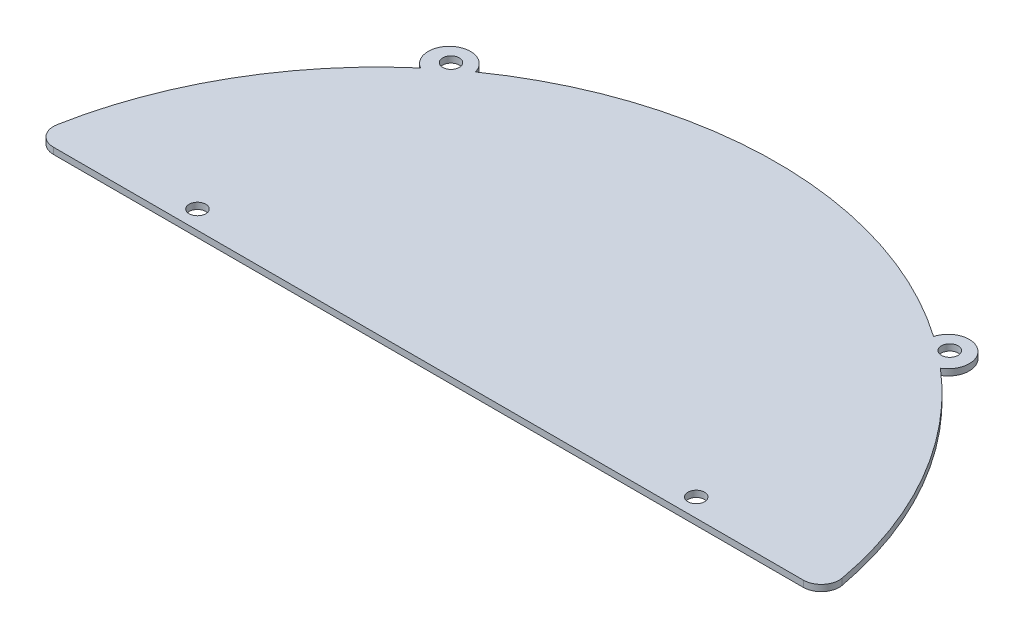
SolidWorks part; units mm, degrees
ref_plane "Plan de face" through (0, 0, 0) normal (0, 0, 1) x (1, 0, 0)
ref_plane "Plan de dessus" through (0, 0, 0) normal (0, 1, 0) x (1, 0, 0)
ref_plane "Plan de droite" through (0, 0, 0) normal (1, 0, 0) x (0, 0, -1)
sketch "Esquisse1" plane through (0, 0, 0) normal (0, 1, 0) x (1, 0, 0)
  line L0 (-95.25, 0) -> (95.25, 0)
  line L1 (0, 0) -> (0, 83.82) construction
  arc A0 (-95.25, 0) -> (95.25, 0) centre (0, -12.2093) cw
  point P2 (0, 0)
  dimension "D1" = 190.5
  dimension "D2" = 83.82
extrude "Boss.-Extru.1" add sketch "Esquisse1" along normal blind 1.524 contours A0 L0
fillet "Congé1" radius 4.318 2 edges at (-95.25, 0.762, 0) (95.25, 0.762, 0)
sketch "Esquisse2" plane through (0, 1.524, 0) normal (0, 1, 0) x (1, 0, 0)
  line L0 (55.1106, 66.432) -> (62.5462, 60.6577) construction
  line L1 (55.1106, 66.432) -> (62.1105, 61.0294)
  line L3 (60, 1.5535) -> (60, 65.0535) construction
  line L4 (0, 0) -> (0, 107.9902) construction
  line L5 (-62.5462, 60.6577) -> (-55.1106, 66.432)
  arc A3 (62.5462, 60.6577) -> (55.1106, 66.432) centre (60, 65.0535) ccw
  arc A4 (94.4571, 5.0961) -> (-94.4571, 5.0961) centre (0, -12.2093) ccw construction
  arc A6 (-62.5462, 60.6577) -> (-55.1106, 66.432) centre (-60, 65.0535) cw
  dimension "D1" = 60
  dimension "D2" = 10.16
  dimension "D4" = 63.5
extrude "Boss.-Extru.3" add sketch "Esquisse2" against normal up to surface (1.524 mm away) up to face at (0, 0, -21.7317)
sketch "Esquisse3" plane through (0, 1.524, 0) normal (0, 1, 0) x (1, 0, 0)
  line L0 (0, 83.82) -> (0, 0) construction
  line L1 (60, 0) -> (60, 4.445) construction
  line L2 (-90.2098, 0) -> (90.2098, 0) construction
  line L3 (60, 4.445) -> (0, 4.445) construction
  line L4 (-60, 4.445) -> (-60, 65.445) construction
  arc A1 (55.1106, 66.432) -> (-55.1106, 66.432) centre (0, -12.2093) ccw construction
  circle A3 centre (60, 4.445) radius 2
  circle A5 centre (-60, 4.445) radius 2
  circle A6 centre (-60, 65.445) radius 2
  circle A7 centre (60, 65.445) radius 2
  dimension "D2" = 4
  dimension "D3" = 60
  dimension "D5" = 4
  dimension "D1" = 4.445
  dimension "D4" = 61
extrude "Enlèv. mat.-Extru.1" cut sketch "Esquisse3" against normal through all
